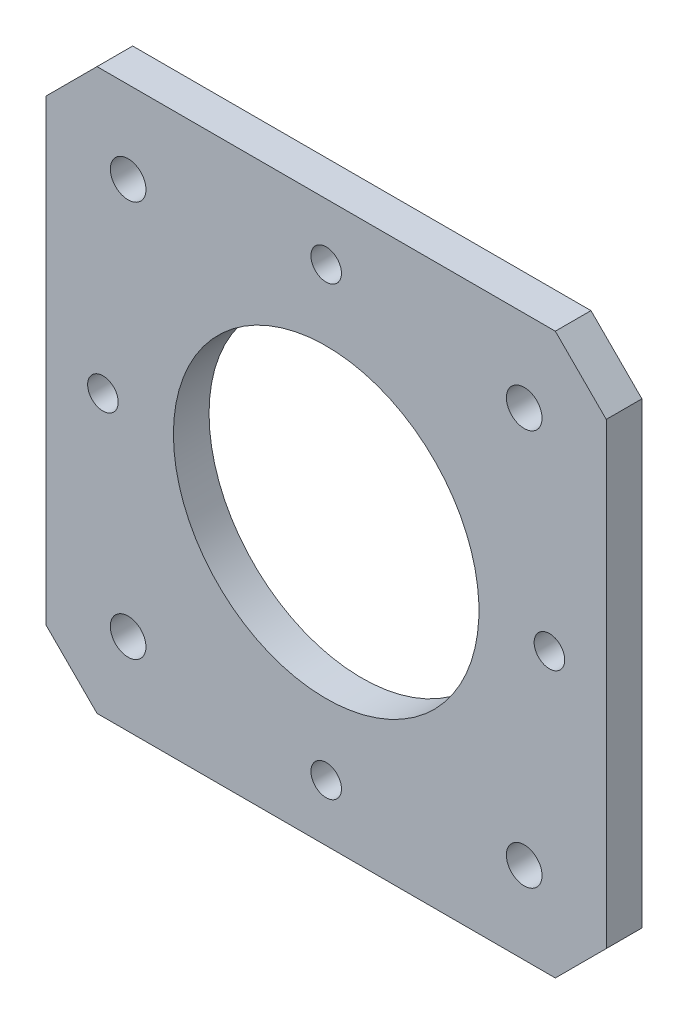
SolidWorks part; units mm, degrees
ref_plane "Front Plane" through (0, 0, 0) normal (0, 0, 1) x (1, 0, 0)
ref_plane "Top Plane" through (0, 0, 0) normal (0, 1, 0) x (1, 0, 0)
ref_plane "Right Plane" through (0, 0, 0) normal (1, 0, 0) x (0, 0, -1)
sketch "Sketch1" plane through (0, 0, 0) normal (0, 0, 1) x (1, 0, 0)
  line L1 (-27.5, 27.5) -> (27.5, 27.5)
  line L2 (-27.5, 27.5) -> (-27.5, -27.5)
  line L3 (-27.5, -27.5) -> (27.5, -27.5)
  line L4 (27.5, 27.5) -> (27.5, -27.5)
  line L5 (-27.5, 27.5) -> (27.5, -27.5) construction
  line L6 (-27.5, -27.5) -> (27.5, 27.5) construction
  circle A0 centre (0, 0) radius 27.5 construction
  circle A1 centre (19.4454, 19.4454) radius 1.75
  circle A2 centre (-19.4454, 19.4454) radius 1.75
  circle A3 centre (-19.4454, -19.4454) radius 1.75
  circle A4 centre (19.4454, -19.4454) radius 1.75
  point P0 (0, 0)
  dimension "D1" = 55
  dimension "D2" = 3.5
extrude "Boss-Extrude1" add sketch "Sketch1" along normal blind 3.5
sketch "Sketch2" plane through (0, 0, 0) normal (0, 0, -1) x (-1, 0, 0)
  circle A0 centre (0, 0) radius 15
  dimension "D1" = 30
extrude "Cut-Extrude1" cut sketch "Sketch2" against normal through all
sketch "Sketch3" plane through (0, 0, 0) normal (0, 0, -1) x (-1, 0, 0)
  line L0 (0, 29.6985) -> (-29.6985, 0) construction
  line L1 (0, 29.6985) -> (29.6985, 0) construction
  line L2 (-29.6985, 0) -> (0, -29.6985) construction
  line L3 (29.6985, 0) -> (0, -29.6985) construction
  line L4 (0, 29.6985) -> (0, -29.6985) construction
  line L5 (-29.6985, 0) -> (29.6985, 0) construction
  line L6 (0, 21.9203) -> (-21.9203, 0) construction
  line L7 (0, 21.9203) -> (21.9203, 0) construction
  line L8 (-21.9203, 0) -> (0, -21.9203) construction
  line L9 (21.9203, 0) -> (0, -21.9203) construction
  line L10 (0, 21.9203) -> (0, -21.9203) construction
  line L11 (-21.9203, 0) -> (21.9203, 0) construction
  circle A0 centre (0, 21.9203) radius 1.5
  circle A1 centre (21.9203, 0) radius 1.5
  circle A2 centre (0, -21.9203) radius 1.5
  circle A3 centre (-21.9203, 0) radius 1.5
  point P1 (0, 0)
  point P2 (0, 0)
  dimension "D3" = 3
  dimension "D1" = 42
  dimension "D2" = 31
extrude "Cut-Extrude2" cut sketch "Sketch3" against normal through all contours A0 | A3 | A2 | A1
chamfer "Chamfer1" distance 5 angle 45 4 edges at (-27.5, -27.5, 1.75) (27.5, -27.5, 1.75) (-27.5, 27.5, 1.75) (27.5, 27.5, 1.75)
